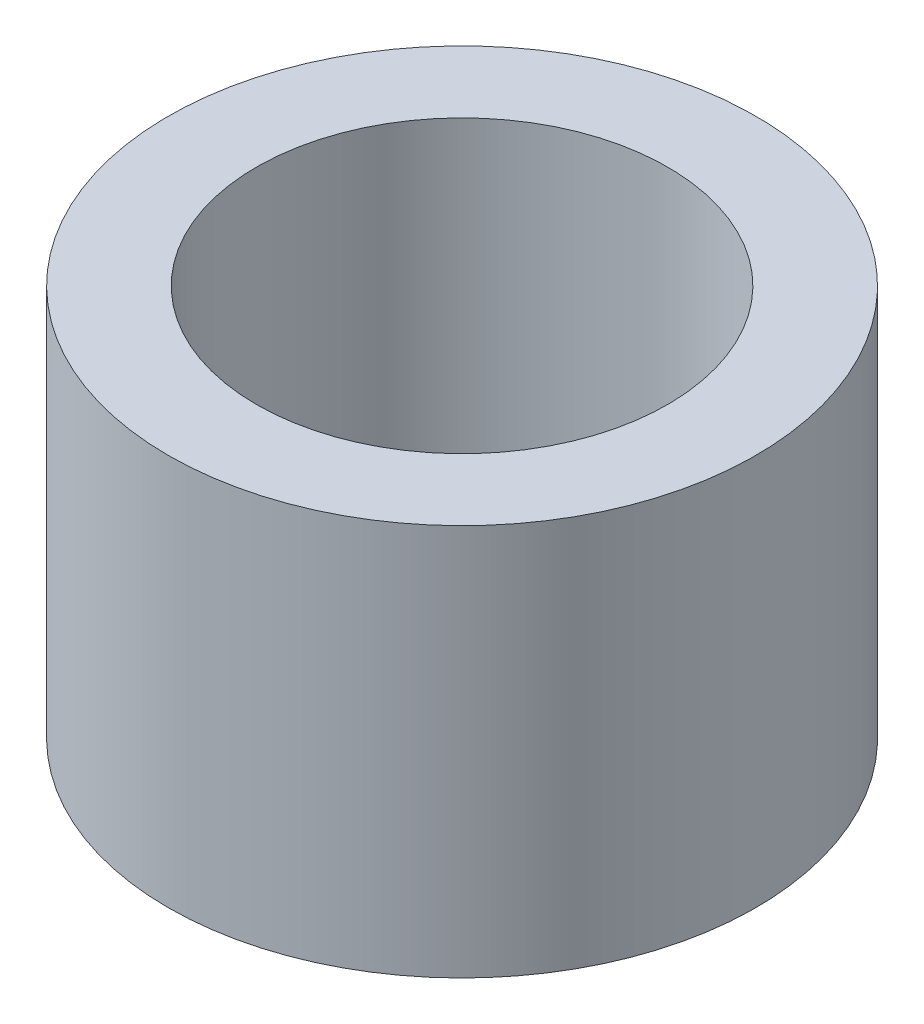
SolidWorks part; units mm, degrees
ref_plane "正面" through (0, 0, 0) normal (0, 0, 1) x (1, 0, 0)
ref_plane "平面" through (0, 0, 0) normal (0, 1, 0) x (1, 0, 0)
ref_plane "右側面" through (0, 0, 0) normal (1, 0, 0) x (0, 0, -1)
sketch "ｽｹｯﾁ1" plane through (0, 0, 0) normal (0, 1, 0) x (1, 0, 0)
  circle A0 centre (0, 0) radius 2.1
  circle A1 centre (0, 0) radius 3
  dimension "D1" = 6
  dimension "D2" = 4.2
extrude "ﾎﾞｽ - 押し出し1" add sketch "ｽｹｯﾁ1" along normal blind 4
